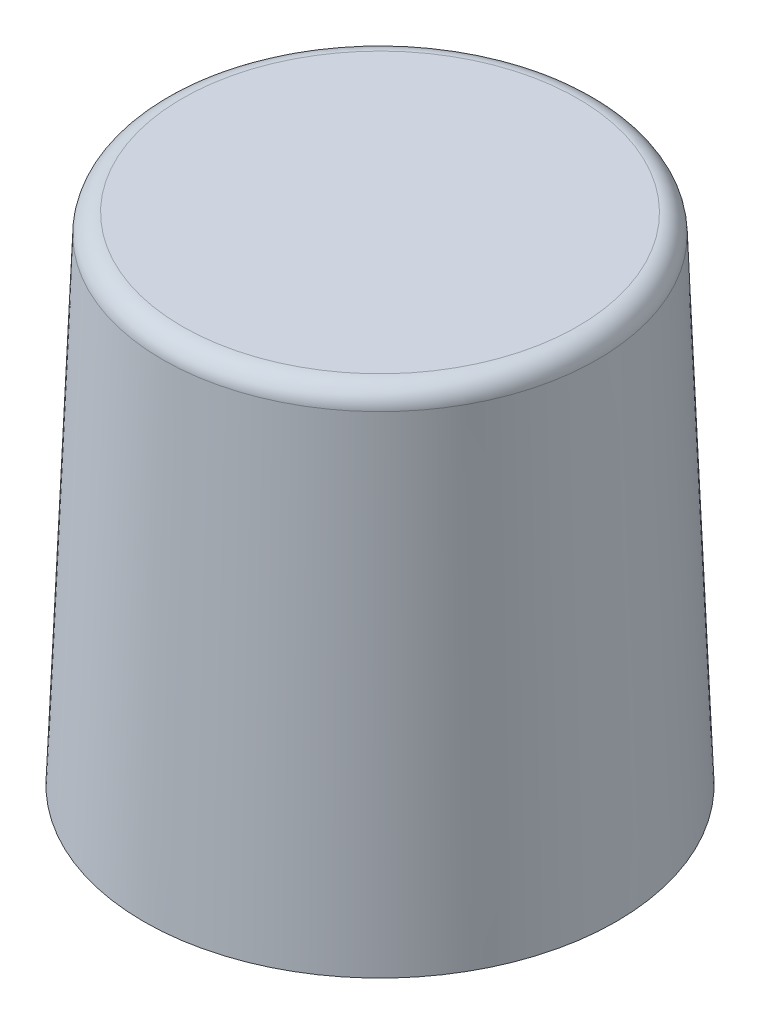
SolidWorks part; units mm, degrees
material "Silicon Rubber"
ref_plane "Front" through (0, 0, 0) normal (0, 0, 1) x (1, 0, 0)
ref_plane "Top" through (0, 0, 0) normal (0, 1, 0) x (1, 0, 0)
ref_plane "Right" through (0, 0, 0) normal (1, 0, 0) x (0, 0, -1)
sketch "Sketch1" plane through (0, 0, 0) normal (0, 0, 1) x (1, 0, 0)
  line L0 (0, 0) -> (2.75, 0)
  line L1 (2.75, 0) -> (3, -6.3)
  line L2 (3, -6.3) -> (1.5, -6.3)
  line L3 (1.5, -6.3) -> (1.5, -0.3)
  line L4 (1.5, -0.3) -> (0, -0.3)
  line L5 (0, -0.3) -> (0, 0)
  line L6 (0, 0) -> (0, 10.7204) construction
  point P8 (1.302, -15.9891)
  dimension "D1" = 5.5
  dimension "D2" = 6
  dimension "D3" = 6.3
  dimension "D4" = 6
  dimension "D5" = 3
revolve "Revolve1" add sketch "Sketch1" angle 360 about L6
fillet "Fillet1" radius 0.25 1 edges at (0, 0, -2.75)
